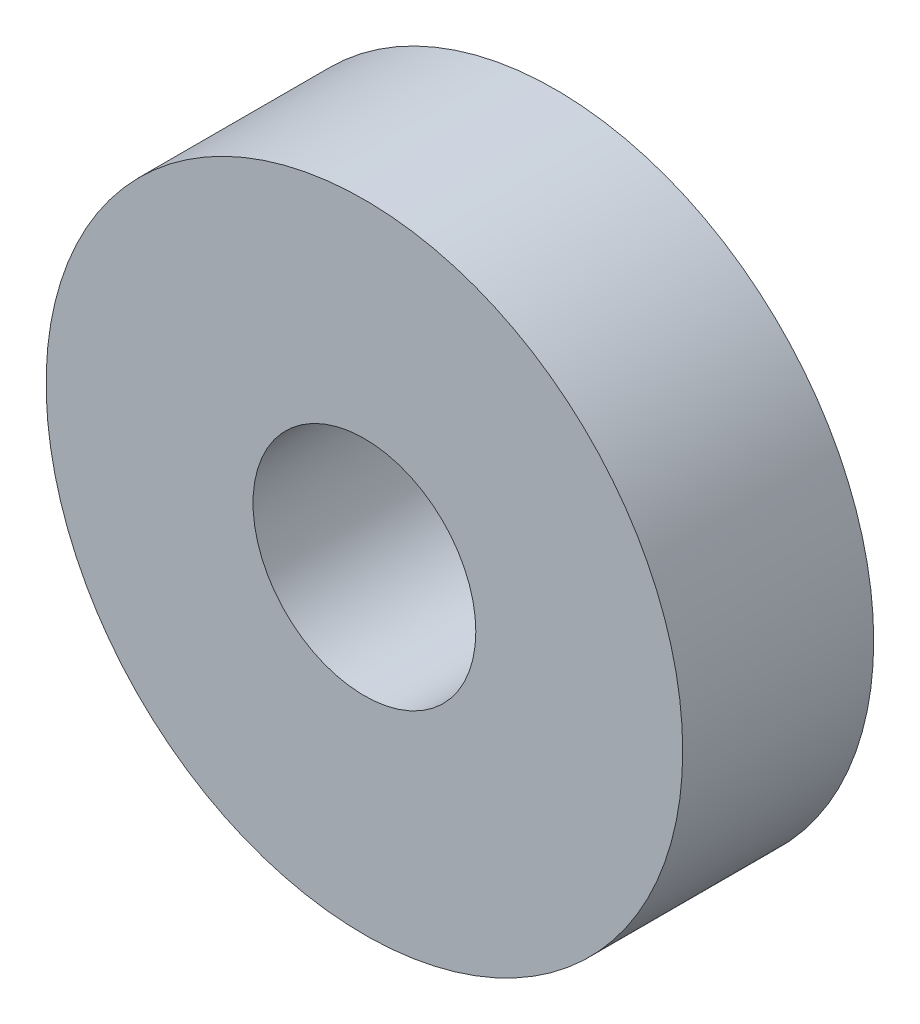
SolidWorks part; units mm, degrees
ref_plane "Front Plane" through (0, 0, 0) normal (0, 0, 1) x (1, 0, 0)
ref_plane "Top Plane" through (0, 0, 0) normal (0, 1, 0) x (1, 0, 0)
ref_plane "Right Plane" through (0, 0, 0) normal (1, 0, 0) x (0, 0, -1)
sketch "Sketch2" plane through (0, 0, 0) normal (0, 0, 1) x (1, 0, 0)
  circle A0 centre (0, 0) radius 5
  circle A1 centre (0, 0) radius 1.75
  dimension "D1" = 3.5
  dimension "D2" = 10
extrude "Boss-Extrude1" add sketch "Sketch2" along normal blind 3
